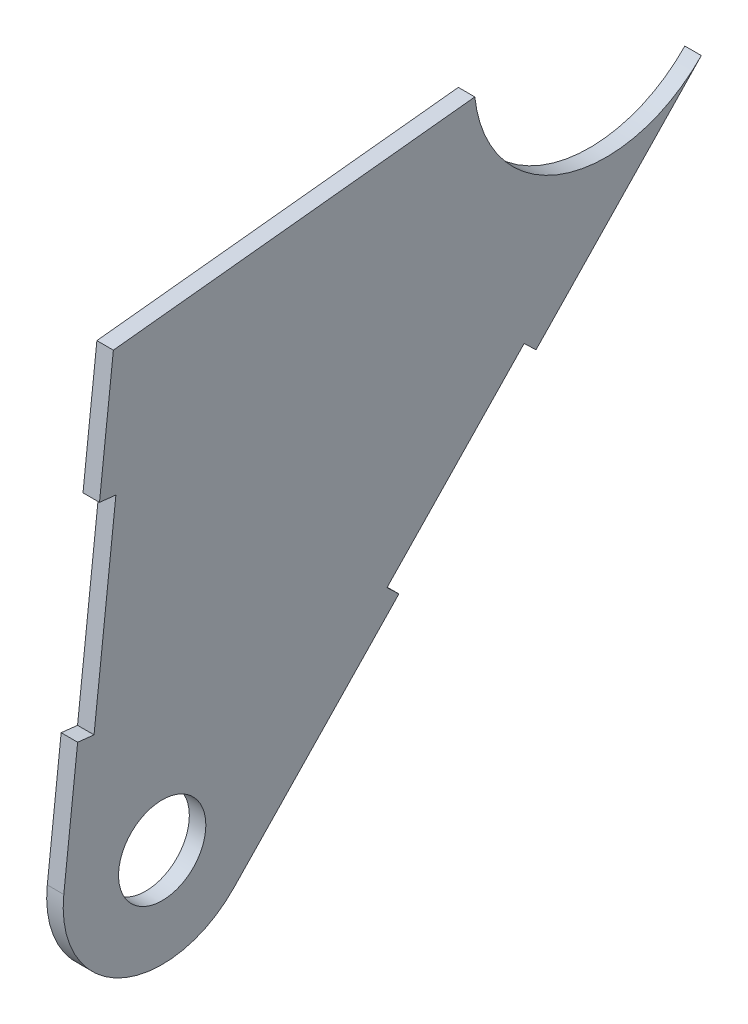
SolidWorks part; units mm, degrees
material "AISI 4130 Steel, annealed at 865C"
ref_plane "X-Y Datum" through (0, 0, 0) normal (0, 0, 1) x (1, 0, 0)
ref_plane "X-Z Datum" through (0, 0, 0) normal (0, 1, 0) x (1, 0, 0)
ref_plane "Y-Z Datum" through (0, 0, 0) normal (1, 0, 0) x (0, 0, -1)
sketch "Sketch1" plane through (0, 0, 0) normal (1, 0, 0) x (0, 0, -1)
  line L0 (-9.4668, 1.0509) -> (-8.1328, 13.0677)
  line L1 (-4.6969, 44.0181) -> (30.0789, 47.7289)
  line L3 (51.8693, 40.2817) -> (35.9664, 23.7144)
  line L5 (22.7744, 9.9713) -> (6.8716, -6.596)
  line L7 (-8.1328, 13.0677) -> (-6.555, 12.8925)
  line L8 (-6.0309, 32.0014) -> (-4.4531, 31.8262)
  line L9 (-6.555, 12.8925) -> (-4.4531, 31.8262)
  line L11 (22.7744, 9.9713) -> (21.6292, 11.0706)
  line L12 (35.9664, 23.7144) -> (34.8212, 24.8138)
  line L13 (21.6292, 11.0706) -> (34.8212, 24.8138)
  line L14 (-6.0309, 32.0014) -> (-4.6969, 44.0181)
  line L15 (42.7072, 49.0763) -> (-4.6969, 44.0181) construction
  arc A0 (-9.4668, 1.0509) -> (6.8716, -6.596) centre (0, 0) ccw
  arc A2 (51.8693, 40.2817) -> (30.0789, 47.7289) centre (42.7072, 49.0763) cw
  dimension "D1" = 9.525
  dimension "D2" = 12.7
  dimension "D3" = 1.5875
  dimension "D5" = 19.05
extrude "Boss-Extrude1" add sketch "Sketch1" along normal blind 1.5875
hole_wizard "M8 Clearance Hole1" positions "Sketch2" profile "Sketch3" hole size "M8" standard "ANSI Metric" end condition through all
sketch "Sketch2" plane through (1.5875, 0, 0) normal (1, 0, 0) x (0, 0, -1)
  point P0 (0, 0)
sketch "Sketch3" plane through (1.5875, 0, 0) normal (0, 1, 0) x (0, 0, -1)
  line L0 (0, 0) -> (0, 1.5875)
  line L1 (0, 1.5875) -> (4.2, 1.5875)
  line L2 (4.2, 1.5875) -> (4.2, 0)
  line L5 (4.2, 0) -> (0, 0)
  line L11 (0, -6.35) -> (0, 107.95) construction
  dimension "Thru Hole Dia." = 8.4
  dimension "Thru Hole Depth" = 1.5875
